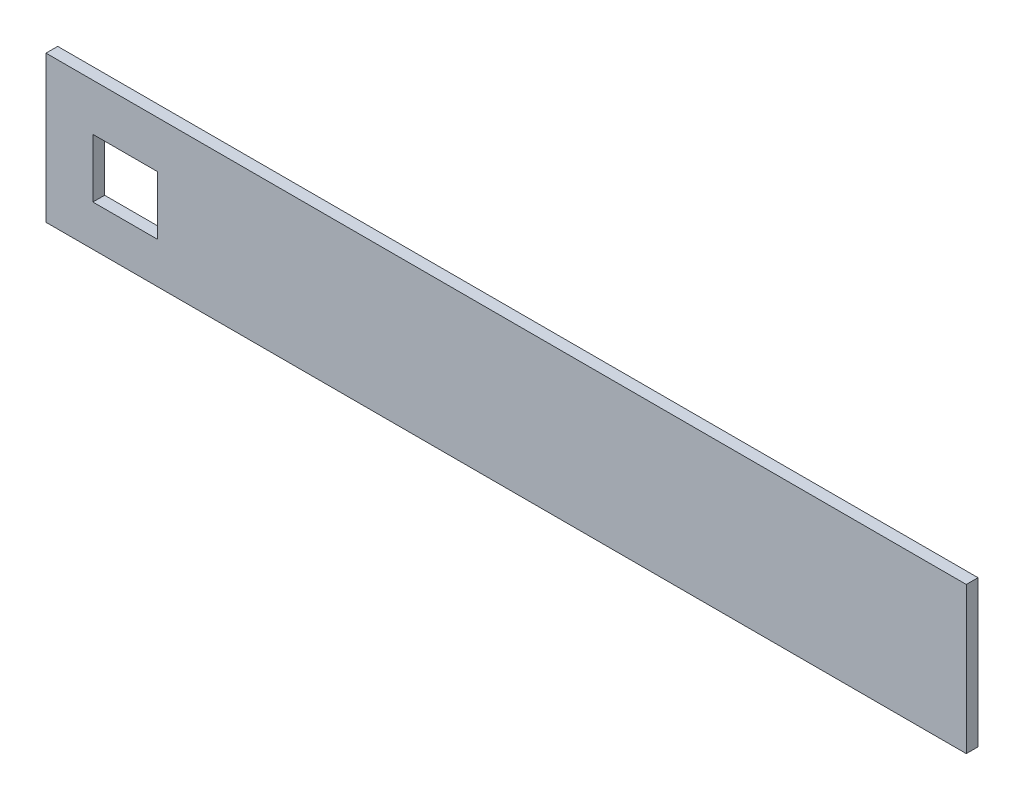
SolidWorks part; units mm, degrees
ref_plane "Front Plane" through (0, 0, 0) normal (0, 0, 1) x (1, 0, 0)
ref_plane "Top Plane" through (0, 0, 0) normal (0, 1, 0) x (1, 0, 0)
ref_plane "Right Plane" through (0, 0, 0) normal (1, 0, 0) x (0, 0, -1)
sketch "Sketch1" plane through (0, 0, 0) normal (0, 0, 1) x (1, 0, 0)
  line L1 (-78.5, 12.5) -> (78.5, 12.5)
  line L2 (-78.5, 12.5) -> (-78.5, -12.5)
  line L3 (-78.5, -12.5) -> (78.5, -12.5)
  line L4 (78.5, 12.5) -> (78.5, -12.5)
  line L5 (-78.5, 12.5) -> (78.5, -12.5) construction
  line L6 (-78.5, -12.5) -> (78.5, 12.5) construction
  point P0 (0, 0)
  dimension "D1" = 25
  dimension "D2" = 157
extrude "Boss-Extrude1" add sketch "Sketch1" along normal blind 2
sketch "Sketch2" plane through (0, 0, 2) normal (0, 0, 1) x (1, 0, 0)
  line L0 (-78.5, -12.5) -> (78.5, -12.5) construction
  line L1 (-70.5, 4.5) -> (-59.5, 4.5)
  line L2 (-70.5, 4.5) -> (-70.5, -5.5)
  line L3 (-70.5, -5.5) -> (-59.5, -5.5)
  line L4 (-59.5, 4.5) -> (-59.5, -5.5)
  line L5 (-78.5, 12.5) -> (-78.5, -12.5) construction
  dimension "D1" = 11
  dimension "D2" = 10
  dimension "D3" = 7
  dimension "D4" = 8
extrude "Cut-Extrude1" cut sketch "Sketch2" against normal through all
